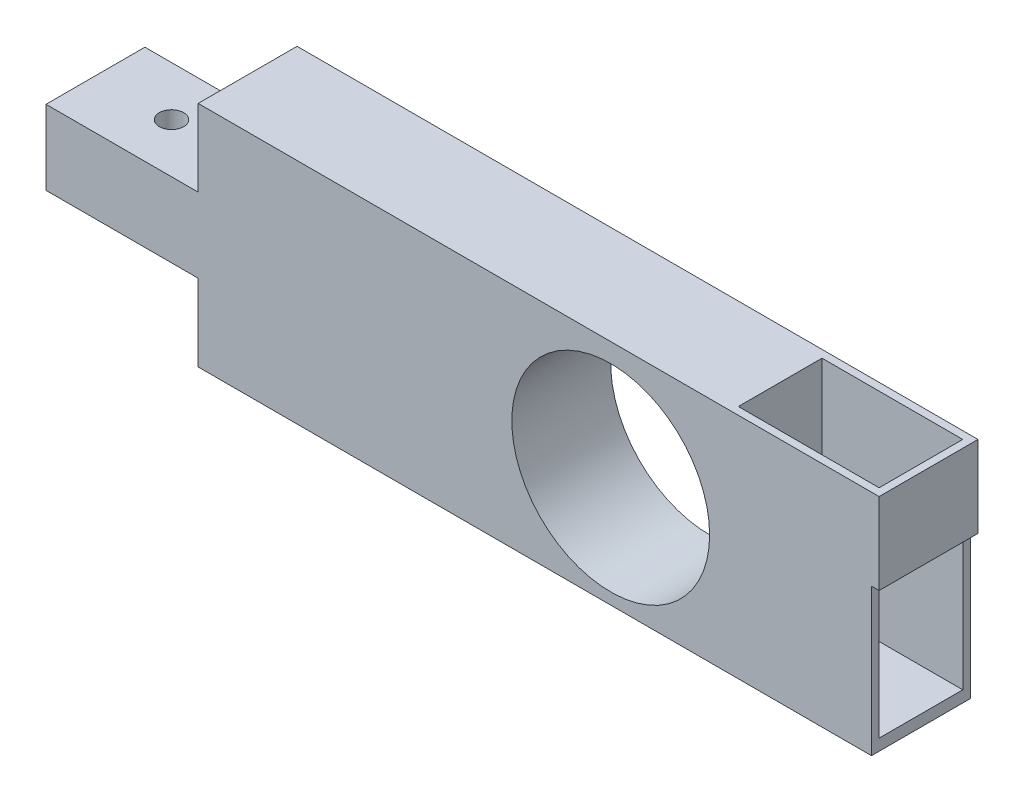
SolidWorks part; units mm, degrees
ref_plane "Front Plane" through (0, 0, 0) normal (0, 0, 1) x (1, 0, 0)
ref_plane "Top Plane" through (0, 0, 0) normal (0, 1, 0) x (1, 0, 0)
ref_plane "Right Plane" through (0, 0, 0) normal (1, 0, 0) x (0, 0, -1)
sketch "Sketch1" plane through (0, 0, 0) normal (0, 0, 1) x (1, 0, 0)
  line L1 (0, 0) -> (355.325, 0)
  line L2 (0, 0) -> (0, 30)
  line L3 (0, 30) -> (355.325, 30)
  line L4 (355.325, 0) -> (355.325, 30)
  line L5 (50, 0) -> (250, 0)
  line L6 (50, 0) -> (50, -17)
  line L7 (50, -17) -> (250, -17)
  line L8 (250, 0) -> (250, -17)
  line L9 (0, 0) -> (355.325, 0)
  line L10 (0, 0) -> (0, -17)
  line L11 (0, -17) -> (355.325, -17)
  line L12 (355.325, 0) -> (355.325, -17)
  line L13 (0, 0) -> (177.6625, 0)
  line L14 (0, 0) -> (0, -17)
  line L15 (0, -17) -> (177.6625, -17)
  line L16 (177.6625, 0) -> (177.6625, -17)
  line L17 (0, 0) -> (50, 0)
  line L18 (0, 0) -> (0, -5)
  line L19 (0, -5) -> (50, -5)
  line L20 (50, 0) -> (50, -5)
  circle A0 centre (20.775, 14.5) radius 12.5
  circle A1 centre (334.55, 14.5) radius 12.5
  circle A2 centre (60, -2.5) radius 1
  circle A3 centre (68, -2.5) radius 1
  circle A4 centre (60, -14.5) radius 1
  circle A5 centre (68, -14.5) radius 1
  dimension "D1" = 25
  dimension "D11" = 2
  dimension "D2" = 313.775
  dimension "D3" = 20.775
  dimension "D4" = 20.775
  dimension "D5" = 30
  dimension "D6" = 15.5
  dimension "D7" = 15.5
  dimension "D8" = 17
  dimension "D9" = 50
  dimension "D10" = 200
  dimension "D12" = 8
  dimension "D13" = 12
  dimension "D14" = 8
  dimension "D15" = 12
  dimension "D16" = 10
  dimension "D17" = 10
  dimension "D18" = 2.5
  dimension "D19" = 2.5
  dimension "D20" = 5
extrude "Boss-Extrude3" add sketch "Sketch1" along normal blind 13 contours L1 L9 L4 L3 L2 A1 A0 | L16 L1 L6 L7 A5 A4 A3 A2 | L10 L19 L6 L1
fillet "Fillet3" radius 5 6 edges at (355.325, 0, 6.5) (355.325, 30, 6.5) (177.6625, -17, 6.5) (50, -17, 6.5) (0, -5, 6.5) (0, 30, 6.5)
sketch "Sketch3" plane through (0, 0, 13) normal (0, 0, 1) x (1, 0, 0)
  line L0 (0, 0) -> (0, 25) construction
  circle A0 centre (85, 14.5) radius 12.5
  circle A1 centre (165, 14.5) radius 12.5
  circle A2 centre (245, 14.5) radius 12.5
  dimension "D1" = 25
  dimension "D2" = 85
  dimension "D3" = 80
  dimension "D4" = 80
extrude "Boss-Extrude4" add sketch "Sketch3" along normal blind 13
sketch "Sketch4" plane through (0, 0, 0) normal (0, 0, -1) x (-1, 0, 0)
  circle A0 centre (-68, -2.5) radius 1.425
  circle A1 centre (-60, -2.5) radius 1.425
  circle A2 centre (-60, -14.5) radius 1.425
  circle A3 centre (-68, -14.5) radius 1.425
  dimension "D1" = 2.85
extrude "Cut-Extrude1" cut sketch "Sketch4" against normal up to next
sketch "Sketch5" plane through (0, 0, 0) normal (0, 0, -1) x (-1, 0, 0)
  line L1 (-177.6625, 0) -> (-113.8325, 0)
  line L2 (-177.6625, 0) -> (-177.6625, -18)
  line L3 (-177.6625, -18) -> (-113.8325, -18)
  line L4 (-113.8325, 0) -> (-113.8325, -18)
  dimension "D1" = 63.83
  dimension "D2" = 18
extrude "Cut-Extrude3" cut sketch "Sketch5" against normal through all
fillet "Fillet4" radius 5 1 edges at (113.8325, -17, 6.5)
sketch "Sketch6" plane through (0, 0, 13) normal (0, 0, 1) x (1, 0, 0)
  line L1 (50, 0) -> (113.8325, 0)
  line L2 (50, 0) -> (50, -17)
  line L3 (50, -17) -> (113.8325, -17)
  line L4 (113.8325, 0) -> (113.8325, -17)
extrude "Cut-Extrude4" cut sketch "Sketch6" against normal blind 5
sketch "Sketch7" plane through (0, 0, 8) normal (0, 0, 1) x (1, 0, 0)
  circle A0 centre (60, -2.5) radius 1
  circle A1 centre (68, -2.5) radius 1
  circle A2 centre (68, -14.5) radius 1
  circle A3 centre (60, -14.5) radius 1
  circle A4 centre (60, -14.5) radius 2.1596
  circle A5 centre (60, -2.5) radius 2.1171
  circle A6 centre (68, -2.5) radius 1.9161
  circle A7 centre (68, -14.5) radius 2.4159
  dimension "D1" = 2
extrude "Boss-Extrude5" add sketch "Sketch7" against normal blind 8
sketch "Sketch8" plane through (0, 0, 26) normal (0, 0, 1) x (1, 0, 0)
  circle A0 centre (85, 14.5) radius 12.5
  circle A1 centre (165, 14.5) radius 12.5
  circle A2 centre (245, 14.5) radius 12.5
extrude "Boss-Extrude6" add sketch "Sketch8" along normal blind 13
sketch "Sketch10" plane through (0, 0, 13) normal (0, 0, 1) x (1, 0, 0)
  line L0 (50, 0) -> (350.325, 0) construction
  line L4 (285.325, 30) -> (285.325, 19.9)
  line L5 (5, 30) -> (350.325, 30) construction
  line L6 (285.325, 19.9) -> (265.325, 19.9)
  line L8 (285.325, 10.1) -> (265.325, 10.1)
  line L9 (265.325, 19.9) -> (265.325, 10.1)
  line L11 (55, -17) -> (108.8325, -17) construction
  line L12 (113.8325, -12) -> (113.8325, 0) construction
  line L13 (113.8325, 0) -> (50, 0) construction
  line L14 (50, 0) -> (50, -5) construction
  line L15 (50, -5) -> (50, -12) construction
  line L16 (50, -5) -> (50, 0) construction
  line L17 (350.325, 30) -> (5, 30) construction
  line L18 (0, 25) -> (0, 0) construction
  line L19 (5, -5) -> (50, -5) construction
  line L20 (55, -17) -> (108.8325, -17)
  line L21 (113.8325, -12) -> (113.8325, 0)
  line L22 (113.8325, 0) -> (50, 0)
  line L23 (50, 0) -> (50, -5)
  line L24 (50, -5) -> (50, -12)
  line L25 (50, -5) -> (50, 0)
  line L26 (50, 0) -> (285.325, 0)
  line L28 (285.325, 30) -> (5, 30)
  line L29 (0, 25) -> (0, 0)
  line L30 (5, -5) -> (50, -5)
  line L31 (285.325, 10.1) -> (285.325, 0)
  arc A0 (108.8325, -17) -> (113.8325, -12) centre (108.8325, -12) ccw construction
  arc A1 (50, -12) -> (55, -17) centre (55, -12) ccw construction
  circle A2 centre (334.55, 14.5) radius 13
  arc A4 (5, 30) -> (0, 25) centre (5, 25) ccw construction
  arc A5 (0, 0) -> (5, -5) centre (5, 0) ccw construction
  arc A6 (108.8325, -17) -> (113.8325, -12) centre (108.8325, -12) ccw
  arc A7 (50, -12) -> (55, -17) centre (55, -12) ccw
  arc A10 (5, 30) -> (0, 25) centre (5, 25) ccw
  arc A11 (0, 0) -> (5, -5) centre (5, 0) ccw
  line M4 (50, -5) -> (50, 0)
  line M5 (50, 0) -> (350.325, 0)
  line M9 (350.325, 30) -> (5, 30)
  arc M10 (5, 30) -> (0, 25) centre (5, 25) ccw
  line M11 (0, 25) -> (0, 0)
  arc M12 (0, 0) -> (5, -5) centre (5, 0) ccw
  line M13 (5, -5) -> (50, -5)
  circle M14 centre (245, 14.5) radius 12.5
  circle M15 centre (165, 14.5) radius 12.5
  circle M16 centre (85, 14.5) radius 12.5
  circle M17 centre (334.55, 14.5) radius 12.5
  circle M18 centre (20.775, 14.5) radius 12.5
  dimension "D1" = 26
  dimension "D2" = 20
  dimension "D3" = 9.8
  dimension "D4" = 10.1
extrude "Cut-Extrude5" cut sketch "Sketch10" against normal through all and the other way through all contours L31 L8 L9 L6 L4 M9 M10 M11 M12 M13 M4 M5 M14 M16 M18 M15 | A2 M17 | M16 | M15 | M14 | L24 A7 L20 A6 L21 M5 M4
sketch "Sketch13" plane through (285.325, 0, 0) normal (-1, 0, 0) x (0, 0, 1)
  line L1 (0, 30) -> (13, 30)
  line L2 (0, 30) -> (0, 0)
  line L3 (0, 0) -> (13, 0)
  line L4 (13, 30) -> (13, 0)
extrude "Boss-Extrude7" add sketch "Sketch13" along normal blind 5
sketch "Sketch14" plane through (265.325, 0, 0) normal (-1, 0, 0) x (0, 0, 1)
  line L1 (0, 19.9) -> (13, 19.9)
  line L2 (0, 19.9) -> (0, 10.1)
  line L3 (0, 10.1) -> (13, 10.1)
  line L4 (13, 19.9) -> (13, 10.1)
extrude "Boss-Extrude8" add sketch "Sketch14" along normal blind 5
sketch "Sketch15" plane through (0, 19.9, 0) normal (0, 1, 0) x (1, 0, 0)
  line L0 (280.325, 0) -> (260.325, 0) construction
  line L1 (260.325, -13) -> (260.325, 0) construction
  circle A0 centre (270.325, -6.5) radius 1.6
  dimension "D1" = 3.2
  dimension "D2" = 6.5
  dimension "D3" = 10
extrude "Cut-Extrude6" cut sketch "Sketch15" against normal through all
sketch "Sketch17" plane through (0, 0, 13) normal (0, 0, 1) x (1, 0, 0)
  line L1 (350.325, 30) -> (355.325, 30)
  line L2 (350.325, 30) -> (350.325, 0)
  line L3 (350.325, 0) -> (355.325, 0)
  line L4 (355.325, 30) -> (355.325, 0)
  dimension "D1" = 5
  dimension "D2" = 30
extrude "Cut-Extrude7" cut sketch "Sketch17" against normal through all
sketch "Sketch18" plane through (350.325, 0, 0) normal (1, 0, 0) x (0, 0, -1)
  line L1 (0, 30) -> (0, 0) construction
  line L3 (-11.25, 30) -> (-11.25, 1.5)
  line L4 (-11.25, 1.5) -> (-1.75, 1.5)
  line L5 (-1.75, 30) -> (-1.75, 1.5)
  line L6 (0, 0) -> (-13, 0) construction
  line L8 (-11.25, 30) -> (-13, 30)
  line L9 (-13, 30) -> (-13, 0)
  line L10 (-13, 0) -> (0, 0)
  line L11 (0, 0) -> (0, 30)
  line L12 (0, 30) -> (-1.75, 30)
  dimension "D1" = 9.5
  dimension "D2" = 1.75
  dimension "D3" = 1.5
extrude "Boss-Extrude9" add sketch "Sketch18" along normal blind 18.5
sketch "Sketch19" plane through (368.825, 0, 0) normal (1, 0, 0) x (0, 0, -1)
  line L0 (0, 0) -> (0, 30) construction
  line L1 (-13, 30) -> (0, 30)
  line L2 (-13, 30) -> (-13, 19.3)
  line L3 (-13, 19.3) -> (0, 19.3)
  line L4 (0, 30) -> (0, 19.3)
  line L5 (-13, 0) -> (0, 0) construction
  dimension "D1" = 19.3
extrude "Boss-Extrude10" add sketch "Sketch19" along normal blind 1
sketch "Sketch20" plane through (0, 30, 0) normal (0, 1, 0) x (1, 0, 0)
  line L0 (368.825, -1.75) -> (368.825, -11.25) construction
  line L1 (350.325, -1.75) -> (368.825, -1.75)
  line L2 (350.325, -1.75) -> (350.325, -1)
  line L3 (350.325, -1) -> (368.825, -1)
  line L4 (368.825, -1.75) -> (368.825, -1)
  line L5 (350.325, -11.25) -> (368.827, -11.25)
  line L6 (350.325, -11.25) -> (350.325, -12)
  line L7 (350.325, -12) -> (368.827, -12)
  line L8 (368.827, -11.25) -> (368.827, -12)
  dimension "D1" = 0.75
  dimension "D2" = 0.75
extrude "Cut-Extrude8" cut sketch "Sketch20" against normal up to surface (28.5 mm away) up to face at (359.575, 1.5, 6.5)
